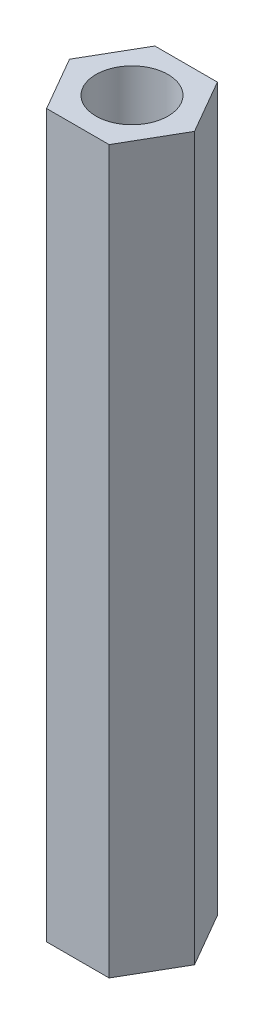
SolidWorks part; units mm, degrees
ref_plane "前视基准面" through (0, 0, 0) normal (0, 0, 1) x (1, 0, 0)
ref_plane "上视基准面" through (0, 0, 0) normal (0, 1, 0) x (1, 0, 0)
ref_plane "右视基准面" through (0, 0, 0) normal (1, 0, 0) x (0, 0, -1)
sketch "草图1" plane through (0, 0, 0) normal (0, 1, 0) x (1, 0, 0)
  line L0 (-1.73, 3) -> (1.73, 3)
  line L1 (1.7331, 2.9982) -> (3.4631, 0.0018)
  line L2 (3.4631, -0.0018) -> (1.7331, -2.9982)
  line L3 (1.73, -3) -> (-1.73, -3)
  line L4 (-1.7331, -2.9982) -> (-3.4631, -0.0018)
  line L5 (-3.4631, 0.0018) -> (-1.7331, 2.9982)
  line L6 (-1.7331, -2.9982) -> (-1.7321, -3)
  line L7 (-1.73, -3) -> (-1.7321, -3)
  line L8 (-3.4631, 0.0018) -> (-3.4641, 0)
  line L9 (-3.4631, -0.0018) -> (-3.4641, 0)
  line L10 (-1.73, 3) -> (-1.7321, 3)
  line L11 (-1.7331, 2.9982) -> (-1.7321, 3)
  line L12 (1.7331, 2.9982) -> (1.7321, 3)
  line L13 (1.73, 3) -> (1.7321, 3)
  line L14 (3.4631, -0.0018) -> (3.4641, 0)
  line L15 (3.4631, 0.0018) -> (3.4641, 0)
  line L16 (1.73, -3) -> (1.7321, -3)
  line L17 (1.7331, -2.9982) -> (1.7321, -3)
  circle A0 centre (0, 0) radius 3 construction
  circle A1 centre (0, 0) radius 2
  point P6 (0, 3)
  point P20 (0, 0)
  point P36 (0, 0)
  dimension "D1" = 4
  dimension "D2" = 6
  dimension "D3" = 3.46
  dimension "D4" = 6
  dimension "D5" = 6
extrude "凸台-拉伸2" add sketch "草图1" along normal blind 40
